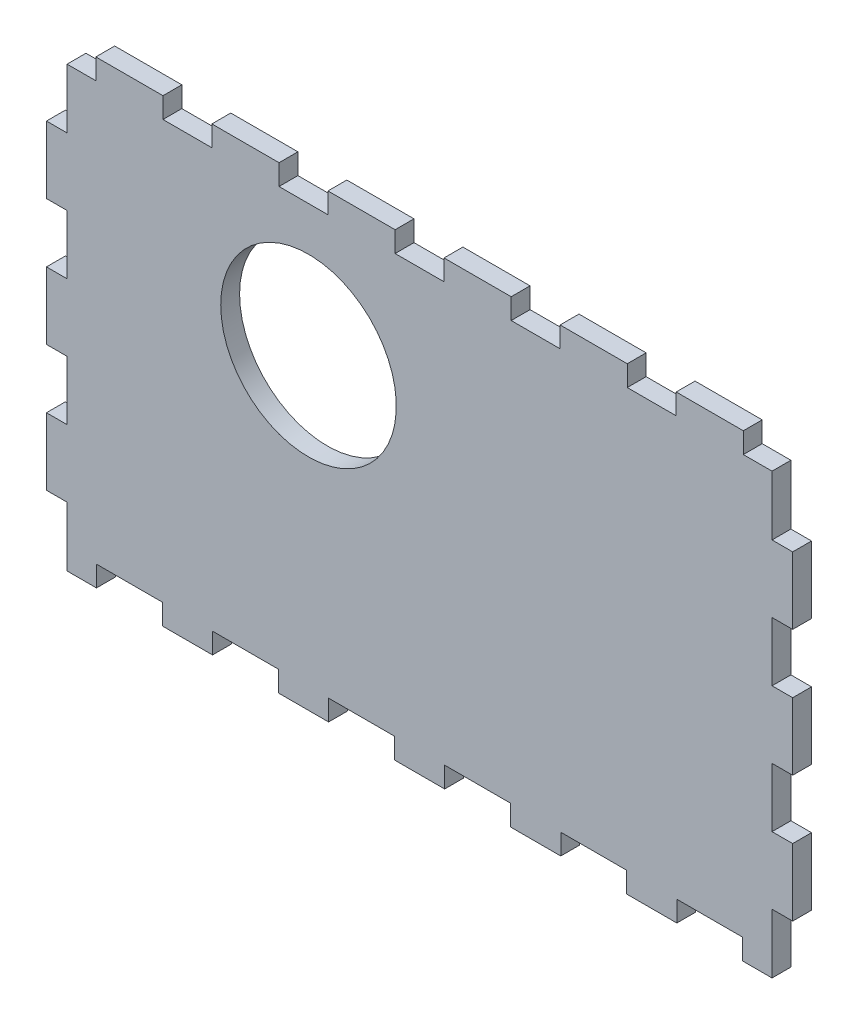
SolidWorks part; units mm, degrees
ref_plane "Front Plane" through (0, 0, 0) normal (0, 0, 1) x (1, 0, 0)
ref_plane "Top Plane" through (0, 0, 0) normal (0, 1, 0) x (1, 0, 0)
ref_plane "Right Plane" through (0, 0, 0) normal (1, 0, 0) x (0, 0, -1)
sketch "Sketch2" plane through (0, 0, 0) normal (0, 0, 1) x (1, 0, 0)
  line L0 (80.3, 100) -> (80.3, 0) construction
  line L1 (0, 0) -> (6.693, 0)
  line L2 (0, 0) -> (0, 13.575)
  line L3 (0, 100) -> (6.543, 100)
  line L4 (160.6, 0) -> (160.6, 13.575)
  line L5 (160.6, 86.425) -> (160.6, 100)
  line L6 (160.6, 86.425) -> (165.3, 86.425)
  line L8 (160.6, 71.125) -> (165.3, 71.125)
  line L9 (165.3, 86.425) -> (165.3, 71.125)
  line L10 (160.6, 42.35) -> (165.3, 42.35)
  line L11 (160.6, 57.65) -> (165.3, 57.65)
  line L12 (165.3, 57.65) -> (165.3, 42.35)
  line L13 (160.6, 13.575) -> (165.3, 13.575)
  line L14 (160.6, 28.875) -> (165.3, 28.875)
  line L15 (165.3, 28.875) -> (165.3, 13.575)
  line L16 (160.6, 57.65) -> (160.6, 71.125)
  line L17 (160.6, 28.875) -> (160.6, 42.35)
  line L18 (0, 13.575) -> (-4.7, 13.575)
  line L19 (-4.7, 28.875) -> (-4.7, 13.575)
  line L20 (0, 28.875) -> (-4.7, 28.875)
  line L21 (-4.7, 57.65) -> (-4.7, 42.35)
  line L22 (0, 57.65) -> (-4.7, 57.65)
  line L23 (0, 86.425) -> (-4.7, 86.425)
  line L24 (-4.7, 86.425) -> (-4.7, 71.125)
  line L25 (0, 71.125) -> (-4.7, 71.125)
  line L26 (0, 42.35) -> (-4.7, 42.35)
  line L27 (0, 86.425) -> (0, 100)
  line L28 (0, 57.65) -> (0, 71.125)
  line L29 (0, 28.875) -> (0, 42.35)
  line L30 (21.843, 100) -> (32.986, 100)
  line L32 (6.543, 100) -> (6.543, 104.7)
  line L33 (6.543, 104.7) -> (21.843, 104.7)
  line L34 (21.843, 100) -> (21.843, 104.7)
  line L35 (48.286, 100) -> (48.286, 104.7)
  line L36 (32.986, 104.7) -> (48.286, 104.7)
  line L37 (32.986, 100) -> (32.986, 104.7)
  line L38 (74.729, 100) -> (74.729, 104.7)
  line L39 (59.429, 104.7) -> (74.729, 104.7)
  line L40 (59.429, 100) -> (59.429, 104.7)
  line L41 (101.172, 100) -> (101.172, 104.7)
  line L42 (85.872, 104.7) -> (101.172, 104.7)
  line L43 (85.872, 100) -> (85.872, 104.7)
  line L44 (127.615, 100) -> (127.615, 104.7)
  line L45 (112.315, 104.7) -> (127.615, 104.7)
  line L46 (112.315, 100) -> (112.315, 104.7)
  line L47 (154.058, 100) -> (154.058, 104.7)
  line L48 (138.758, 104.7) -> (154.058, 104.7)
  line L49 (138.758, 100) -> (138.758, 104.7)
  line L50 (48.286, 100) -> (59.429, 100)
  line L51 (74.729, 100) -> (85.872, 100)
  line L52 (101.172, 100) -> (112.315, 100)
  line L53 (127.615, 100) -> (138.758, 100)
  line L54 (154.058, 100) -> (160.6, 100)
  line L55 (165.3, 50) -> (-4.7, 50) construction
  line L56 (21.693, 0) -> (33.136, 0)
  line L58 (6.693, 0) -> (6.693, 4.7)
  line L59 (6.693, 4.7) -> (21.693, 4.7)
  line L60 (21.693, 0) -> (21.693, 4.7)
  line L61 (48.136, 0) -> (48.136, 4.7)
  line L62 (33.136, 4.7) -> (48.136, 4.7)
  line L63 (33.136, 0) -> (33.136, 4.7)
  line L64 (74.579, 0) -> (74.579, 4.7)
  line L65 (59.579, 4.7) -> (74.579, 4.7)
  line L66 (59.579, 0) -> (59.579, 4.7)
  line L67 (101.022, 0) -> (101.022, 4.7)
  line L68 (86.022, 4.7) -> (101.022, 4.7)
  line L69 (86.022, 0) -> (86.022, 4.7)
  line L70 (127.465, 0) -> (127.465, 4.7)
  line L71 (112.465, 4.7) -> (127.465, 4.7)
  line L72 (112.465, 0) -> (112.465, 4.7)
  line L73 (153.908, 0) -> (153.908, 4.7)
  line L74 (138.908, 4.7) -> (153.908, 4.7)
  line L75 (138.908, 0) -> (138.908, 4.7)
  line L76 (48.136, 0) -> (59.579, 0)
  line L77 (74.579, 0) -> (86.022, 0)
  line L78 (101.022, 0) -> (112.465, 0)
  line L79 (127.465, 0) -> (138.908, 0)
  line L80 (153.908, 0) -> (160.6, 0)
  circle A0 centre (55, 70) radius 20
  point P25 (0, 42.35)
  point P62 (165.3, 78.775)
  point P87 (165.3, 50)
  point P89 (14.193, 104.7)
  point P90 (40.636, 104.7)
  point P91 (14.193, 4.7)
  point P92 (40.636, 4.7)
  dimension "D3" = 40
  dimension "D1" = 100
  dimension "D2" = 160.6
  dimension "D4" = 55
  dimension "D5" = 30
  dimension "D6" = 15.3
  dimension "D7" = 4.7
  dimension "D8" = 21.225
  dimension "D9" = 28.775
  dimension "D11" = 15.3
  dimension "D12" = 4.7
  dimension "D13" = 14.193
  dimension "D14" = 6
  dimension "D15" = 26.443
  dimension "D16" = 50
  dimension "D17" = 15
  dimension "D18" = 14.193
  dimension "D19" = 4.7
  dimension "D20" = 26.443
  dimension "D21" = 6
  dimension "D10" = 3
extrude "Boss-Extrude1" add sketch "Sketch2" along normal blind 4.3
